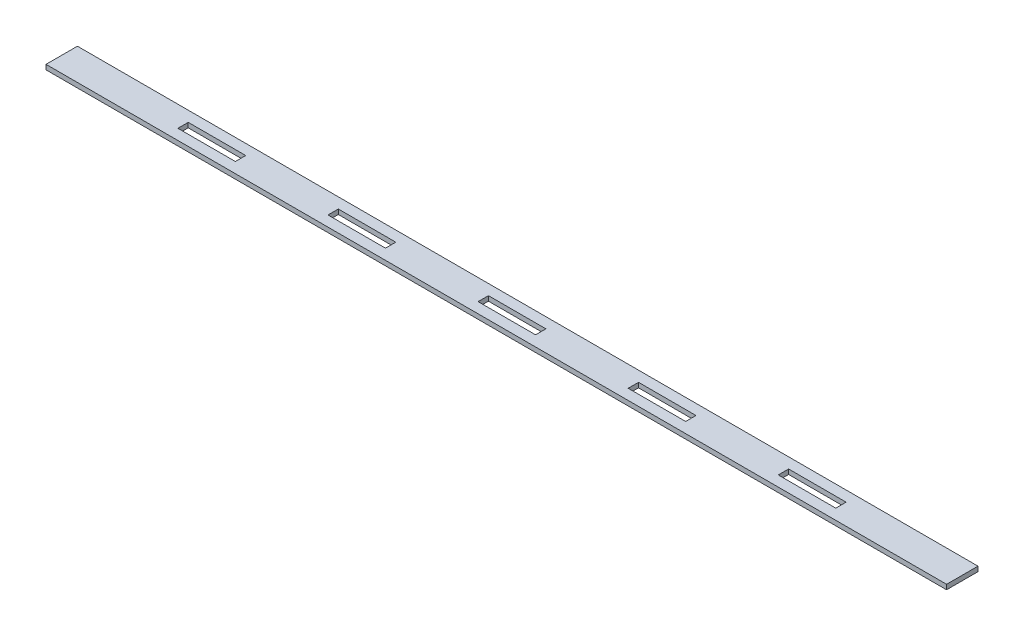
SolidWorks part; units mm, degrees
other "Markup1"
sketch "Sketch4" plane through (-298.45, 3.175, 19.05) normal (-0.3913, 0.9147, 0.101) x (0.9172, 0.3786, 0.1243)
material "Acrylic (Medium-high impact)"
ref_plane "Plan de face" through (0, 0, 0) normal (0, 0, 1) x (1, 0, 0)
ref_plane "Plan de dessus" through (0, 0, 0) normal (0, 1, 0) x (1, 0, 0)
ref_plane "Plan de droite" through (0, 0, 0) normal (1, 0, 0) x (0, 0, -1)
sketch "Sketch1" plane through (0, 0, 0) normal (0, 1, 0) x (1, 0, 0)
  line L1 (298.45, -10.414) -> (-298.45, -10.414)
  line L2 (298.45, -10.414) -> (298.45, 10.414)
  line L3 (298.45, 10.414) -> (-298.45, 10.414)
  line L4 (-298.45, -10.414) -> (-298.45, 10.414)
  line L5 (298.45, -10.414) -> (-298.45, 10.414) construction
  line L6 (298.45, 10.414) -> (-298.45, -10.414) construction
  point P0 (0, 0)
  dimension "D1" = 596.9
  dimension "D2" = 20.828
extrude "Boss-Extrude1" add sketch "Sketch1" along normal blind 3.175
sketch "Sketch5" plane through (0, 3.175, 0) normal (0, 1, 0) x (1, 0, 0)
  line L0 (-298.45, 0) -> (298.45, 0) construction
  line L1 (-218.0167, -3.429) -> (-179.9167, -3.429)
  line L2 (-218.0167, -3.429) -> (-218.0167, 3.429)
  line L3 (-218.0167, 3.429) -> (-179.9167, 3.429)
  line L4 (-179.9167, -3.429) -> (-179.9167, 3.429)
  line L5 (-218.0167, -3.429) -> (-179.9167, 3.429) construction
  line L6 (-218.0167, 3.429) -> (-179.9167, -3.429) construction
  line L7 (298.45, -10.414) -> (298.45, 10.414) construction
  line L8 (-298.45, 10.414) -> (-298.45, -10.414) construction
  line L10 (-118.5333, -3.429) -> (-80.4333, -3.429)
  line L11 (-118.5333, -3.429) -> (-118.5333, 3.429)
  line L12 (-118.5333, 3.429) -> (-80.4333, 3.429)
  line L13 (-80.4333, -3.429) -> (-80.4333, 3.429)
  line L14 (-118.5333, -3.429) -> (-80.4333, 3.429) construction
  line L15 (-118.5333, 3.429) -> (-80.4333, -3.429) construction
  line L16 (-19.05, -3.429) -> (19.05, -3.429)
  line L17 (-19.05, -3.429) -> (-19.05, 3.429)
  line L18 (-19.05, 3.429) -> (19.05, 3.429)
  line L19 (19.05, -3.429) -> (19.05, 3.429)
  line L20 (-19.05, -3.429) -> (19.05, 3.429) construction
  line L21 (-19.05, 3.429) -> (19.05, -3.429) construction
  line L22 (80.4333, -3.429) -> (118.5333, -3.429)
  line L23 (80.4333, -3.429) -> (80.4333, 3.429)
  line L24 (80.4333, 3.429) -> (118.5333, 3.429)
  line L25 (118.5333, -3.429) -> (118.5333, 3.429)
  line L26 (80.4333, -3.429) -> (118.5333, 3.429) construction
  line L27 (80.4333, 3.429) -> (118.5333, -3.429) construction
  line L28 (179.9167, -3.429) -> (218.0167, -3.429)
  line L29 (179.9167, -3.429) -> (179.9167, 3.429)
  line L30 (179.9167, 3.429) -> (218.0167, 3.429)
  line L31 (218.0167, -3.429) -> (218.0167, 3.429)
  line L32 (179.9167, -3.429) -> (218.0167, 3.429) construction
  line L33 (179.9167, 3.429) -> (218.0167, -3.429) construction
  point P0 (-198.9667, 0)
  point P8 (0, 0)
  point P9 (99.4833, 0)
  point P10 (-99.4833, 0)
  point P15 (-99.4833, 3.429)
  point P25 (198.9667, 0)
  point P30 (0, 3.429)
  point P32 (99.4833, 3.429)
  point P35 (0, 0)
  dimension "D1" = 6.858
  dimension "D2" = 99.4833
  dimension "D3" = 38.1
  dimension "D5" = 6.858
  dimension "D6" = 38.1
  dimension "D7" = 6.858
  dimension "D8" = 38.1
  dimension "D9" = 6.858
  dimension "D10" = 38.1
  dimension "D11" = 6.858
  dimension "D12" = 38.1
  dimension "D13" = 99.4833
  dimension "D14" = 99.4833
  dimension "D15" = 99.4833
  dimension "D16" = 99.4833
extrude "Cut-Extrude2" cut sketch "Sketch5" against normal through all
